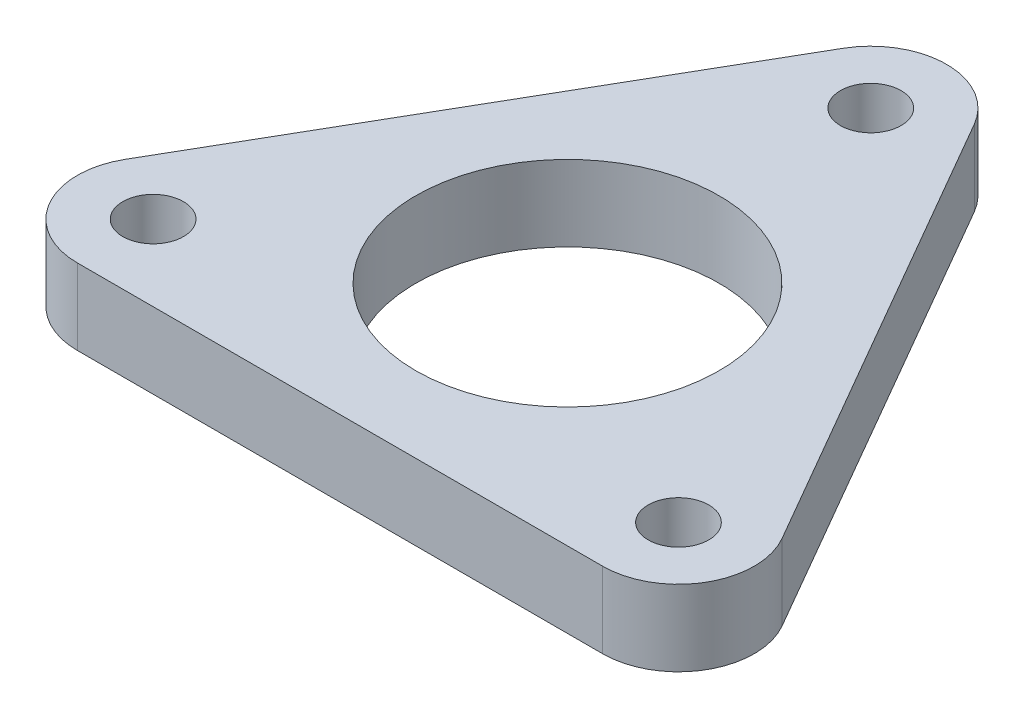
SolidWorks part; units mm, degrees
ref_plane "Plano frontal" through (0, 0, 0) normal (0, 0, 1) x (1, 0, 0)
ref_plane "Plano superior" through (0, 0, 0) normal (0, 1, 0) x (1, 0, 0)
ref_plane "Plano direito" through (0, 0, 0) normal (1, 0, 0) x (0, 0, -1)
sketch "Esboço1" plane through (0, 0, 0) normal (0, 1, 0) x (1, 0, 0)
  line L0 (0, 65.9261) -> (0, -65.9261) construction
  line L1 (-65.9261, 0) -> (65.9261, 0) construction
  line L2 (-51.9615, -30) -> (0, 0)
  line L3 (0, 0) -> (51.9615, -30)
  line L4 (0, 0) -> (0, 60)
  line L5 (-34.641, -30) -> (34.641, -30)
  line L6 (-43.3013, -15) -> (-8.6603, 45)
  line L7 (8.6603, 45) -> (43.3013, -15)
  circle A0 centre (0, 0) radius 40
  circle A1 centre (0, 40) radius 4
  circle A2 centre (-34.641, -20) radius 4
  circle A3 centre (34.641, -20) radius 4
  circle A4 centre (0, 0) radius 20
  arc A8 (-34.641, -30) -> (-43.3013, -15) centre (-34.641, -20) cw
  arc A9 (34.641, -30) -> (43.3013, -15) centre (34.641, -20) ccw
  arc A10 (-8.6603, 45) -> (8.6603, 45) centre (0, 40) cw
  point P19 (0, 0)
  point P22 (0, 0)
  point P25 (0, 0)
  point P26 (-176.6165, 25.3506)
  point P27 (0, 0)
  point P28 (0, 0)
  point P29 (0, 0)
  point P30 (0, 0)
  point P31 (0, 0)
  point P32 (8.3895, 45)
  point P33 (8.6603, 45.4182)
  point P34 (-34.641, -30)
  point P35 (34.641, -30)
  dimension "D1" = 80
  dimension "D2" = 8
  dimension "D6" = 40
  dimension "D7" = 10
  dimension "D3" = 120
  dimension "D4" = 120
  dimension "D5" = 120
  dimension "D8" = 60
extrude "Ressalto-extrusão1" add sketch "Esboço1" along normal blind 10 contours A4 L4 A1 A0 L6 A2 L2 | A10 L6 A0 A1 L4 | A10 L4 A1 A0 L7 | A4 L3 A3 A0 L7 A1 L4 | A4 L2 A2 A0 L5 A3 L3 | A8 L2 A2 A0 L6 | A8 L5 A0 A2 L2 | L3 A9 L7 A0 A3 | L5 A9 L3 A3 A0
